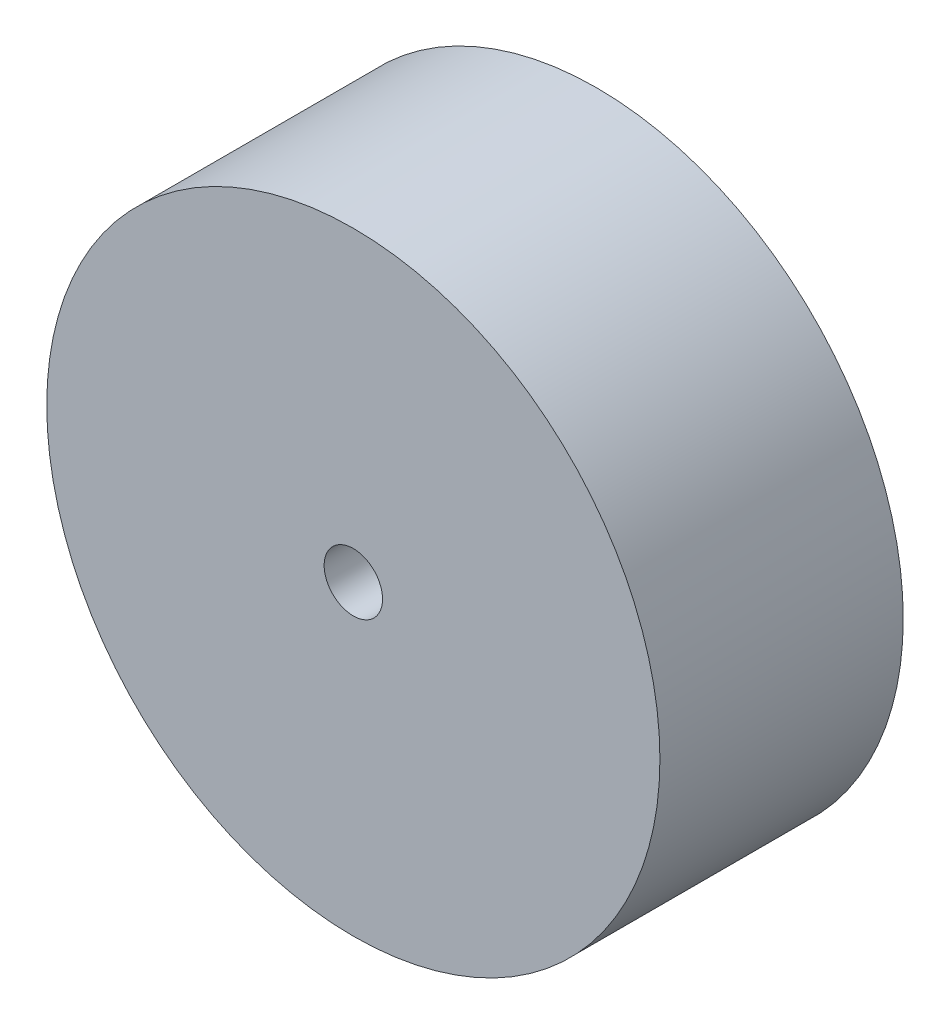
SolidWorks part; units mm, degrees
ref_plane "Plan de face" through (0, 0, 0) normal (0, 0, 1) x (1, 0, 0)
ref_plane "Plan de dessus" through (0, 0, 0) normal (0, 1, 0) x (1, 0, 0)
ref_plane "Plan de droite" through (0, 0, 0) normal (1, 0, 0) x (0, 0, -1)
sketch "Esquisse1" plane through (0, 0, 0) normal (0, 0, 1) x (1, 0, 0)
  circle A0 centre (0, 0) radius 31.5
  dimension "D1" = 63
extrude "Boss.-Extru.1" add sketch "Esquisse1" along normal blind 25
sketch "Esquisse2" plane through (0, 0, 25) normal (0, 0, 1) x (1, 0, 0)
  circle A0 centre (0, 0) radius 3
  dimension "D1" = 6
extrude "Enlèv. mat.-Extru.1" cut sketch "Esquisse2" against normal through all
